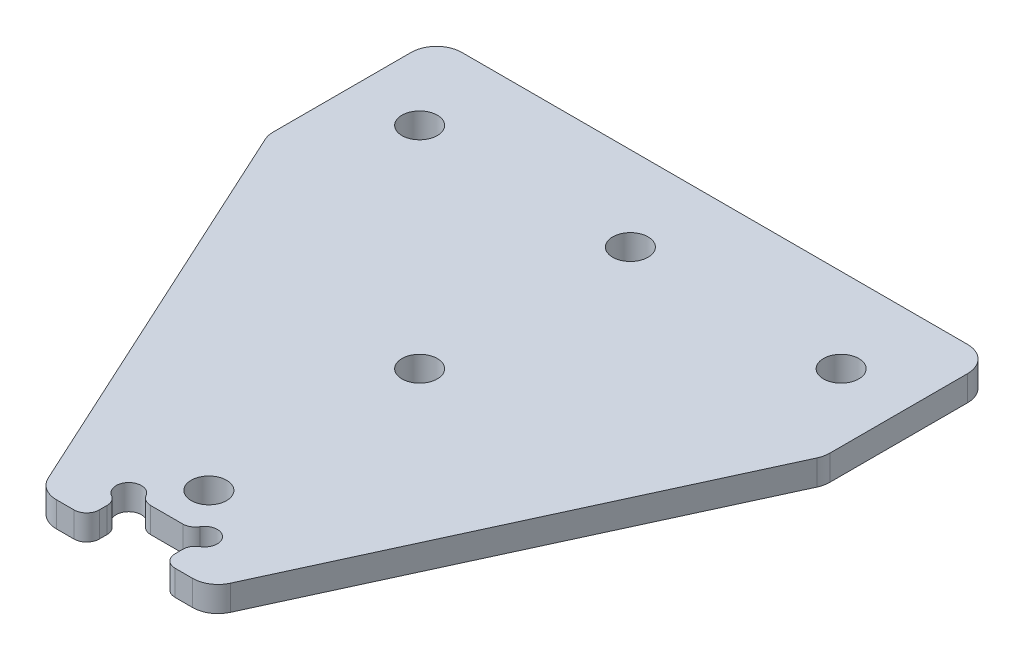
SolidWorks part; units mm, degrees
material "A-玻璃纤维"
ref_plane "前视基准面" through (0, 0, 0) normal (0, 0, 1) x (1, 0, 0)
ref_plane "上视基准面" through (0, 0, 0) normal (0, 1, 0) x (1, 0, 0)
ref_plane "右视基准面" through (0, 0, 0) normal (1, 0, 0) x (0, 0, -1)
sketch "草图1" plane through (0, 0, 0) normal (0, 1, 0) x (1, 0, 0)
  line L0 (-43.2884, 0) -> (46.6978, 0) construction
  line L1 (0, 0) -> (0, -50) construction
  line L2 (33, 10) -> (-33, 10)
  line L3 (-33, 10) -> (-33, -10)
  line L4 (-33, -10) -> (-10, -10)
  line L5 (-10, -10) -> (-10, -60)
  line L6 (-10, -60) -> (10, -60)
  line L7 (10, -60) -> (10, -10)
  line L8 (10, -10) -> (33, -10)
  line L9 (33, -10) -> (33, 10)
  line L10 (-33, -10) -> (-10, -60)
  line L11 (33, -10) -> (10, -60)
  circle A0 centre (0, 0) radius 2.1
  circle A1 centre (25, 0) radius 2.1
  circle A2 centre (-25, 0) radius 2.1
  circle A3 centre (0, -25) radius 2.1
  circle A4 centre (0, -50) radius 2.1
  dimension "D1" = 4.2
  dimension "D2" = 25
  dimension "D3" = 25
  dimension "D4" = 25
  dimension "D5" = 25
  dimension "D7" = 8
  dimension "D6" = 20
  dimension "D8" = 8
  dimension "D9" = 20
  dimension "D10" = 10
extrude "凸台-拉伸1" add sketch "草图1" along normal blind 3
fillet "圆角1" radius 3 6 edges at (33, 1.5, -10) (-33, 1.5, -10) (10, 1.5, 60) (-10, 1.5, 60) (-33, 1.5, 10) (33, 1.5, 10)
sketch "草图2" plane through (0, 3, 0) normal (0, 1, 0) x (1, 0, 0)
  line L0 (-8.0778, -60) -> (8.0778, -60) construction
  line L1 (-4.5, -60) -> (4.5, -60)
  line L2 (-4.5, -60) -> (-4.5, -55)
  line L3 (-4.5, -55) -> (4.5, -55)
  line L4 (4.5, -60) -> (4.5, -55)
  line L5 (0, -55) -> (0, -60) construction
  line L6 (-4.5, -57.5) -> (4.5, -57.5) construction
  circle A0 centre (0, -50) radius 2.1 construction
  point P80 (0, -57.5)
  dimension "D1" = 9
  dimension "D2" = 5
extrude "切除-拉伸1" cut sketch "草图2" against normal blind 3
sketch "草图3" plane through (0, 3, 0) normal (0, 1, 0) x (1, 0, 0)
  circle A0 centre (-4.5, -55) radius 1.5
  circle A1 centre (4.5, -55) radius 1.5
  dimension "D1" = 3
extrude "切除-拉伸2" cut sketch "草图3" against normal blind 10
fillet "圆角2" radius 1.5 6 edges at (3, 1.5, 55) (4.5, 1.5, 56.5) (4.5, 1.5, 60) (-4.5, 1.5, 56.5) (-3, 1.5, 55) (-4.5, 1.5, 60)
